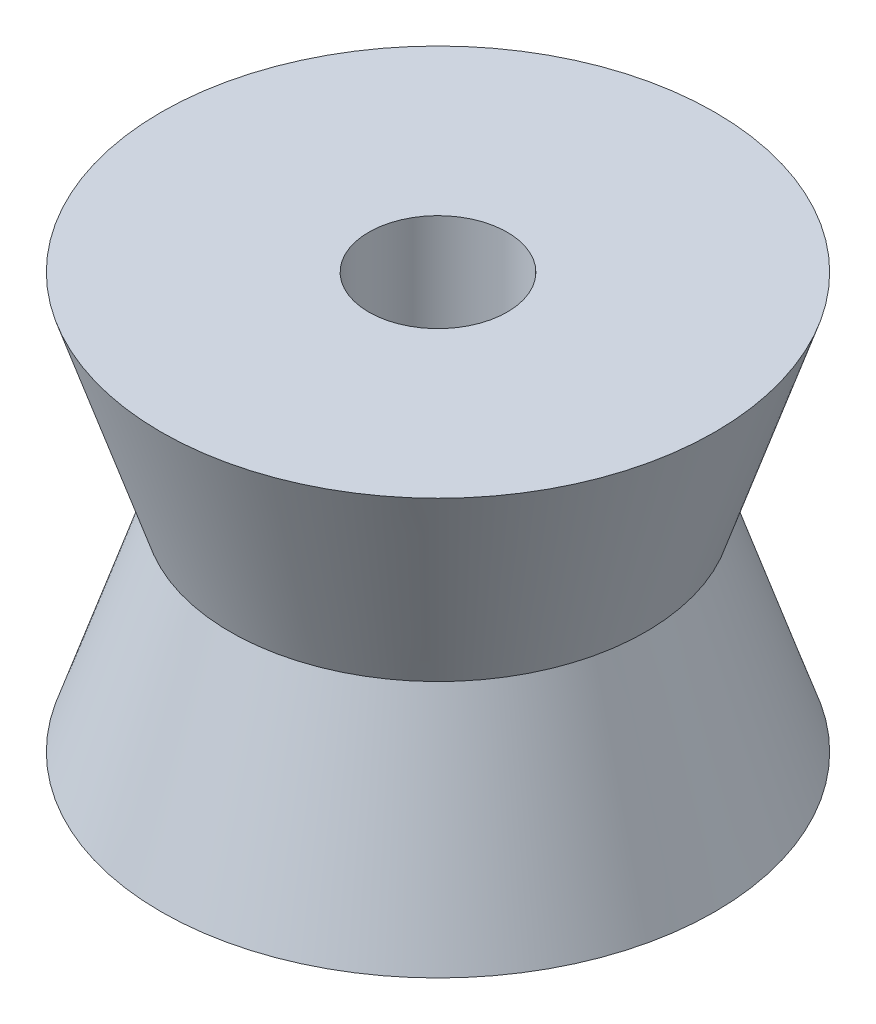
SolidWorks part; units mm, degrees
ref_plane "Front Plane" through (0, 0, 0) normal (0, 0, 1) x (1, 0, 0)
ref_plane "Top Plane" through (0, 0, 0) normal (0, 1, 0) x (1, 0, 0)
ref_plane "Right Plane" through (0, 0, 0) normal (1, 0, 0) x (0, 0, -1)
sketch "Sketch1" plane through (0, 0, 0) normal (0, 0, 1) x (1, 0, 0)
  line L0 (-20, 30) -> (-15, 15)
  line L1 (0, 0) -> (-20, 0)
  line L2 (0, 0) -> (0, 30)
  line L3 (0, 30) -> (-20, 30)
  line L5 (-15, 15) -> (-20, 0)
  dimension "D1" = 30
  dimension "D2" = 20
  dimension "D3" = 15
  dimension "D4" = 20
  dimension "D5" = 5
revolve "Revolve1" add sketch "Sketch1" angle 360 about L2
sketch "Sketch2" plane through (0, 30, 0) normal (0, 1, 0) x (1, 0, 0)
  circle A0 centre (0, 0) radius 5
  dimension "D1" = 10
extrude "Cut-Extrude1" cut sketch "Sketch2" against normal through all
